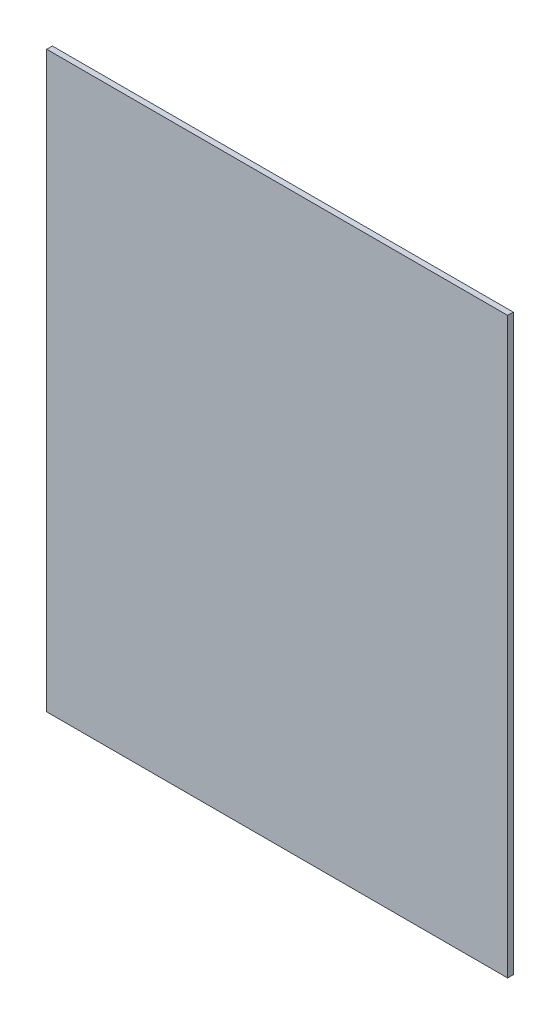
SolidWorks part; units mm, degrees
ref_plane "Front Plane" through (0, 0, 0) normal (0, 0, 1) x (1, 0, 0)
ref_plane "Top Plane" through (0, 0, 0) normal (0, 1, 0) x (1, 0, 0)
ref_plane "Right Plane" through (0, 0, 0) normal (1, 0, 0) x (0, 0, -1)
sketch "Sketch1" plane through (0, 0, 0) normal (0, 0, 1) x (1, 0, 0)
  line L1 (0, 0) -> (400, 0)
  line L2 (0, 0) -> (0, 498)
  line L3 (0, 498) -> (400, 498)
  line L4 (400, 0) -> (400, 498)
  dimension "D1" = 400
  dimension "D2" = 498
extrude "Boss-Extrude1" add sketch "Sketch1" along normal blind 4.9 contours L2 L1 L4 L3
sketch "Sketch2" plane through (0, 0, 4.9) normal (0, 0, 1) x (1, 0, 0)
  line L0 (334.9, 498) -> (334.9, 443.3) construction
  line L1 (0, 498) -> (400, 498) construction
  line L2 (334.9, 443.3) -> (400, 443.3) construction
  line L3 (400, 0) -> (400, 498) construction
  circle A0 centre (334.9, 443.3) radius 10
  dimension "D3" = 20
  dimension "D1" = 65.1
  dimension "D2" = 54.7
extrude "Cut-Extrude1" [suppressed] cut sketch "Sketch2" against normal blind 10
sketch "Sketch3" plane through (0, 0, 4.9) normal (0, 0, 1) x (1, 0, 0)
  line L0 (310, 498) -> (310, 463)
  line L1 (0, 498) -> (400, 498) construction
  line L2 (310, 463) -> (400, 463)
  line L3 (400, 0) -> (400, 498) construction
  line L4 (310, 498) -> (400, 498)
  line L5 (400, 498) -> (400, 463)
  dimension "D1" = 35
  dimension "D2" = 90
extrude "Cut-Extrude2" [suppressed] cut sketch "Sketch3" against normal blind 10
